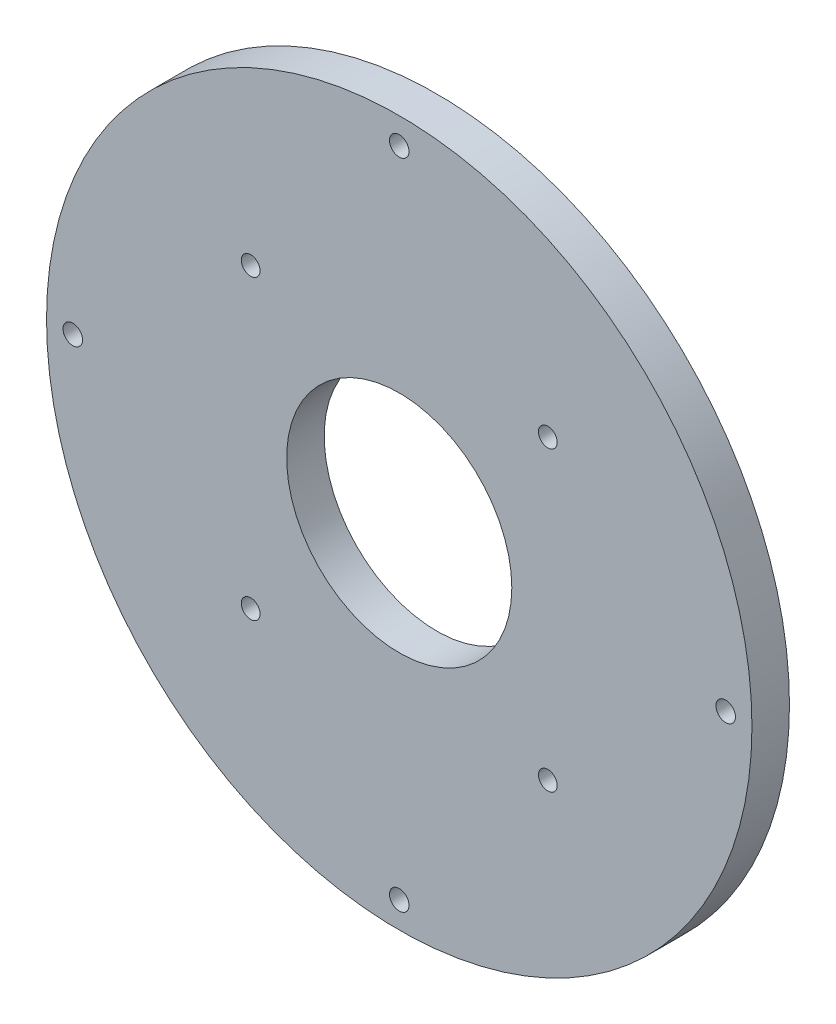
SolidWorks part; units mm, degrees
ref_plane "Front Plane" through (0, 0, 0) normal (0, 0, 1) x (1, 0, 0)
ref_plane "Top Plane" through (0, 0, 0) normal (0, 1, 0) x (1, 0, 0)
ref_plane "Right Plane" through (0, 0, 0) normal (1, 0, 0) x (0, 0, -1)
sketch "Sketch1" plane through (0, 0, 0) normal (0, 0, 1) x (1, 0, 0)
  line L0 (-19.799, 19.799) -> (0, 0) construction
  line L1 (0, 0) -> (0, 28) construction
  circle A0 centre (0, 0) radius 47
  circle A1 centre (0, 0) radius 43.5 construction
  circle A2 centre (0, 43.5) radius 1.3
  circle A3 centre (43.5, 0) radius 1.3
  circle A4 centre (0, -43.5) radius 1.3
  circle A5 centre (-43.5, 0) radius 1.3
  circle A6 centre (0, 0) radius 15
  circle A7 centre (0, 0) radius 28 construction
  circle A8 centre (-19.799, 19.799) radius 1.25
  circle A9 centre (19.799, 19.799) radius 1.25
  circle A10 centre (19.799, -19.799) radius 1.25
  circle A11 centre (-19.799, -19.799) radius 1.25
  point P15 (0, 0)
  point P27 (0, 0)
  dimension "D1" = 94
  dimension "D2" = 87
  dimension "D3" = 2.6
  dimension "D5" = 30
  dimension "D6" = 56
  dimension "D8" = 2.5
  dimension "D7" = 45
  dimension "D4" = 4
  dimension "D9" = 4
extrude "Boss-Extrude1" add sketch "Sketch1" along normal blind 5
